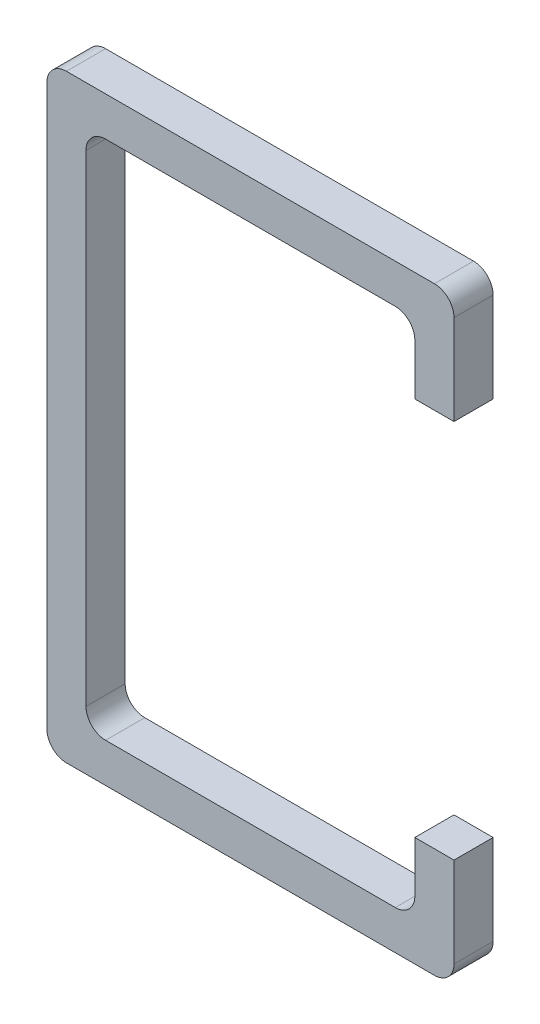
SolidWorks part; units mm, degrees
ref_plane "Front Plane" through (0, 0, 0) normal (0, 0, 1) x (1, 0, 0)
ref_plane "Top Plane" through (0, 0, 0) normal (0, 1, 0) x (1, 0, 0)
ref_plane "Right Plane" through (0, 0, 0) normal (1, 0, 0) x (0, 0, -1)
sketch "Sketch1" plane through (0, 0, 0) normal (0, 0, 1) x (1, 0, 0)
  line L1 (-26.3619, 18.9565) -> (77.6381, 18.9565)
  line L2 (-26.3619, 18.9565) -> (-26.3619, -134.0435)
  line L3 (-26.3619, -134.0435) -> (77.6381, -134.0435)
  line L4 (77.6381, 18.9565) -> (77.6381, -134.0435)
  dimension "D1" = 104
  dimension "D2" = 153
extrude "Boss-Extrude1" add sketch "Sketch1" along normal blind 10
sketch "Sketch2" plane through (0, 0, 10) normal (0, 0, 1) x (1, 0, 0)
  line L0 (-26.3619, 18.9565) -> (-26.3619, -134.0435) construction
  line L1 (-16.3619, 8.9565) -> (67.6381, 8.9565)
  line L2 (-16.3619, 8.9565) -> (-16.3619, -124.0435)
  line L3 (-16.3619, -124.0435) -> (67.6381, -124.0435)
  line L4 (67.6381, 8.9565) -> (67.6381, -124.0435)
  line L5 (-26.3619, -134.0435) -> (77.6381, -134.0435) construction
  line L6 (77.6381, -134.0435) -> (77.6381, 18.9565) construction
  line L7 (77.6381, 18.9565) -> (-26.3619, 18.9565) construction
  dimension "D1" = 10
  dimension "D2" = 10
  dimension "D3" = 10
  dimension "D4" = 10
extrude "Cut-Extrude1" cut sketch "Sketch2" against normal through all both and the other way through all
sketch "Sketch3" plane through (0, 0, 10) normal (0, 0, 1) x (1, 0, 0)
  line L0 (67.6381, -124.0435) -> (67.6381, 8.9565) construction
  line L1 (67.6381, -9.0435) -> (77.6381, -9.0435)
  line L2 (67.6381, -9.0435) -> (67.6381, -106.0435)
  line L3 (67.6381, -106.0435) -> (77.6381, -106.0435)
  line L4 (77.6381, -9.0435) -> (77.6381, -106.0435)
  line L5 (77.6381, -134.0435) -> (77.6381, 18.9565) construction
  line L6 (77.6381, 18.9565) -> (-26.3619, 18.9565) construction
  line L7 (-26.3619, -134.0435) -> (77.6381, -134.0435) construction
  dimension "D1" = 28
  dimension "D2" = 28
extrude "Cut-Extrude3" cut sketch "Sketch3" against normal through all both
fillet "Fillet9" radius 5 1 edges at (-16.3619, 8.9565, 5)
fillet "Fillet10" radius 5 2 edges at (-26.3619, 18.9565, 5) (67.6381, 8.9565, 5)
fillet "Fillet11" radius 5 3 edges at (-26.3619, -134.0435, 5) (77.6381, 18.9565, 5) (67.6381, -124.0435, 5)
fillet "Fillet12" radius 5 2 edges at (77.6381, -134.0435, 5) (-16.3619, -124.0435, 5)
